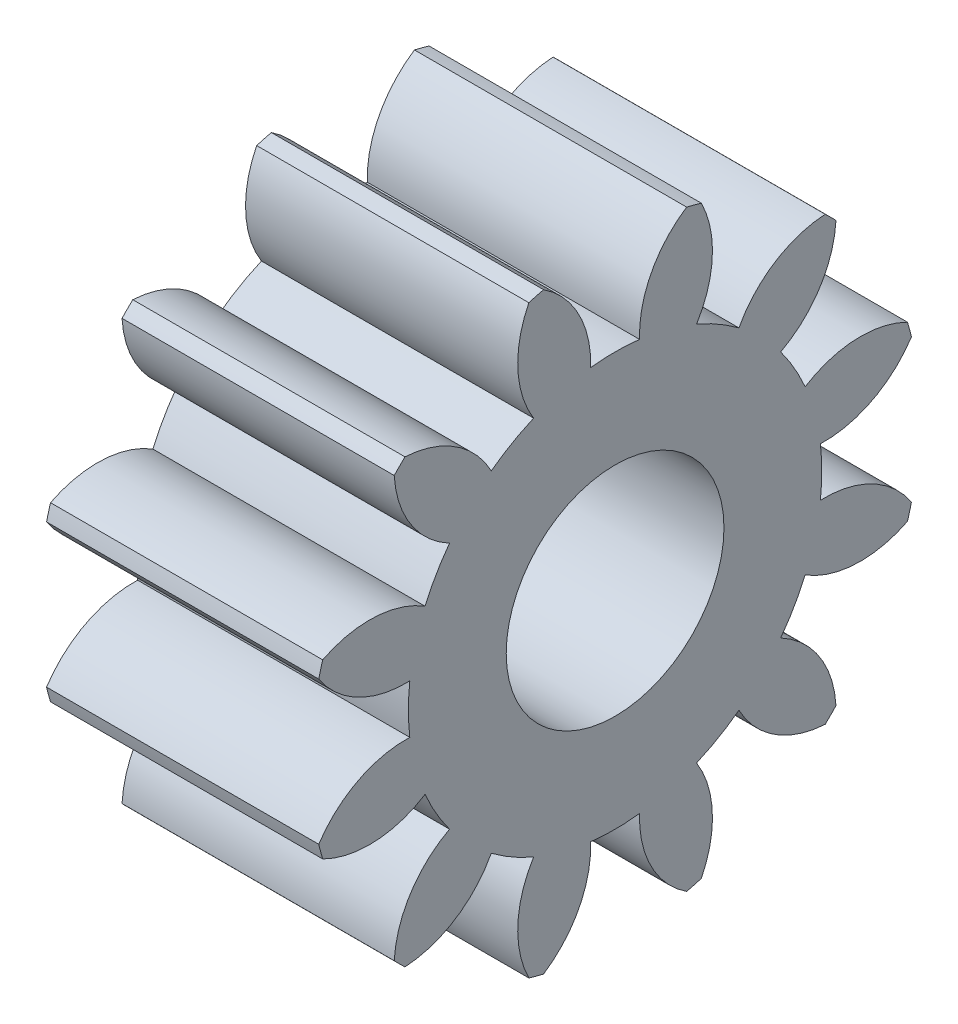
SolidWorks part; units mm, degrees
ref_plane "Plane1" through (0, 0, 0) normal (0, 0, 1) x (1, 0, 0)
ref_plane "Plane2" through (0, 0, 0) normal (0, 1, 0) x (1, 0, 0)
ref_plane "Plane3" through (0, 0, 0) normal (1, 0, 0) x (0, 0, -1)
sketch "HoldingSke" plane through (0, 0, 0) normal (0, 1, 0) x (1, 0, 0)
  line L0 (0, 0) -> (2.4454, -0.5198)
  line L1 (-15, 0) -> (100, 0) construction
  line L2 (0, 0) -> (-2.1039, 2.3779)
  line L3 (0, 0) -> (-11.863, 4.5341)
  line L4 (0, 0) -> (8.4473, 1.7955)
  line L5 (0, 0) -> (-46.8476, -17.4728)
  line L6 (0, 0) -> (-2.0724, -1.3983)
  line L7 (-2.1039, 2.3779) -> (8.6586, 51.2059)
  line L8 (-76.2, 54.61) -> (-75.9, 54.61)
  line L9 (-71.009, 38.7566) -> (-53.1078, 45.2721)
  line L10 (-76.2, 71.12) -> (104.1128, 71.12)
  line L11 (0, 0) -> (-2.5, 0)
  line L12 (-76.2, 101.6) -> (-76.185, 101.6)
  line L13 (24.9733, 27.94) -> (52.9518, 28.4284)
  line L14 (24.9733, 27.94) -> (24.9743, 27.94)
  line L15 (24.9733, 27.94) -> (100.4006, 29.5858)
  line L16 (-63.627, -0.4) -> (-12.827, -0.4)
  circle A0 centre (0, 0) radius 1
  circle A1 centre (0, 0) radius 1.899
  circle A2 centre (0, 0) radius 37.5
  circle A3 centre (0, 0) radius 1
  dimension "MHD" = 3.798
  dimension "Hub_dia" = 75
  dimension "Bore" = 2
  dimension "MBD" = 2
  dimension "Num_teeth" = 12
  dimension "Pitch" = 2.5
  dimension "Overall_len" = 50
  dimension "Show_teeth" = 12
  dimension "Thickness" = 2.5
  dimension "OAL" = 50.0001
  dimension "T_dim" = 0.3
  dimension "Ap" = 20
  dimension "H" = 19.05
  dimension "Pitch_radius" = 180.3128
  dimension "Width" = 2.5
  dimension "Backlash" = 0.015
  dimension "Addendum_fac" = 1
  dimension "Dedendum_fac" = 1.25
  dimension "Clearance_fac" = 0.25
  dimension "Dedendum_add" = 0.001
  dimension "Module" = 0.4
sketch "BasProSke" plane through (0, 0, 0) normal (0, 1, 0) x (1, 0, 0)
  line L0 (-10, 0) -> (60, 0) construction
  line L1 (0, 0) -> (0, 2.8)
  line L2 (0, 0) -> (2.5, 0)
  line L3 (2.5, 0) -> (2.5, 2.8)
  line L4 (2.5, 2.8) -> (0, 2.8)
  dimension "Thickness" = 2.5
  dimension "Diameter" = 5.6
revolve "Base-Revolve" add sketch "BasProSke" angle 360 about L0
sketch "TooCutSke" plane through (0, 0, 0) normal (1, 0, 0) x (0, 0, -1)
  line L1 (0, 0) -> (0, 107) construction
  line L2 (0, 0) -> (-0.3395, 2.3759) construction
  line L3 (0, 0) -> (-1.2334, 4.6032) construction
  line L4 (-0.3395, 2.3759) -> (-0.6167, 2.3016) construction
  arc A0 (0.2246, 1.8857) -> (-0.2246, 1.8857) centre (0, 0) ccw
  arc A1 (0.6868, 2.7407) -> (-0.6868, 2.7407) centre (0, 0) ccw
  circle A2 centre (0, 0) radius 2.4 construction
  circle A3 centre (0, 0) radius 2.2553 construction
  arc A4 (-0.2246, 1.8857) -> (-0.6868, 2.7407) centre (-1.184, 1.9194) ccw
  arc A5 (0.6868, 2.7407) -> (0.2246, 1.8857) centre (1.184, 1.9194) ccw
  dimension "Root_dia" = 3.798
  dimension "Overcut_dia" = 5.6508
  dimension "Pitch_dia" = 4.8
  dimension "Base_dia" = 4.5105
  dimension "Flank_rad" = 0.96
  dimension "Half_ang" = 15
  dimension "Half_CT" = 0.287
extrude "ToothCut" cut sketch "TooCutSke" along normal through all
fillet "Breaks" [suppressed] radius 0.008
fillet "RootFillets" [suppressed] radius 0.101
pattern_circular "TeethCuts" count 12 every 30 about axis through (-10, 0, 0) along (1, 0, 0) of "ToothCut", "RootFillets", "Breaks"
sketch "HubNeaOneSke" plane through (0, 0, 0) normal (-1, 0, 0) x (0, 0, 1)
  circle A0 centre (0, 0) radius 1.899
  dimension "Diameter" = 3.798
extrude "HubNearOne" [suppressed] add sketch "HubNeaOneSke" along normal blind 47.5001
sketch "HubNeaBotSke" plane through (0, 0, 0) normal (-1, 0, 0) x (0, 0, 1)
  circle A0 centre (0, 0) radius 1.899
  dimension "Diameter" = 3.798
extrude "HubNearBoth" [suppressed] add sketch "HubNeaBotSke" along normal blind 23.75
ref_plane "FarPln" through (2.5, 0, 0) normal (1, 0, 0) x (0, 0, -1)
sketch "HubFarSke" plane through (2.5, 0, 0) normal (1, 0, 0) x (0, 0, -1)
  circle A0 centre (0, 0) radius 1.899
  dimension "Diameter" = 3.798
extrude "HubFar" [suppressed] add sketch "HubFarSke" along normal blind 23.75
sketch "BorSke" plane through (0, 0, 0) normal (1, 0, 0) x (0, 0, -1)
  circle A0 centre (0, 0) radius 1
  dimension "Diameter" = 2
extrude "Bore" cut sketch "BorSke" along normal mid plane 100.0001
sketch "KeySke" plane through (0, 0, 0) normal (1, 0, 0) x (0, 0, -1)
  line L0 (-0.4, 0) -> (-0.4, 1.3)
  line L1 (-0.4, 1.3) -> (0.4, 1.3)
  line L2 (0.4, 1.3) -> (0.4, 0)
  line L3 (0, 0) -> (0, 34) construction
  line L4 (-0.4, 0) -> (0.4, 0)
  dimension "Offset" = 1.3
  dimension "Width" = 0.8
extrude "Keyway" [suppressed] cut sketch "KeySke" along normal mid plane 100.0001
pattern_circular "Keyway2" [suppressed] count 2 every 90 about axis through (-10, 0, 0) along (1, 0, 0)
equation "' \"Module@HoldingSke\" = 6.35"
equation "' \"Num_teeth@HoldingSke\" = 12"
equation "' \"Ap@HoldingSke\" =  20"
equation "' \"Ap@HoldingSke\" = 20"
equation "' \"Width@HoldingSke\" = 0.5 * 25.4"
equation "' \"Hub_dia@HoldingSke\"= 1 * 25.4"
equation "' \"Hub_dia@HoldingSke\" = 1 * 25.4"
equation "' \"Overall_len@HoldingSke\" = 1.0 * 25.4"
equation "' \"Bore@HoldingSke\" = 0.75 * 25.4"
equation "' \"T_dim@HoldingSke\" = 0.1 * 25.4"
equation "' \"Width@KeySke\" = 0.25 * 25.4"
equation "' \"Show_teeth@HoldingSke\" = 13"
equation "' \"Backlash@HoldingSke\" = 0.009 * 25.4"
equation "' \"Addendum_fac@HoldingSke\" = 1.0"
equation "' \"Dedendum_fac@HoldingSke\" = 1.25"
equation "' \"Dedendum_add@HoldingSke\" = 0.00005 * 25.4"
equation "' \"Clearance_fac@HoldingSke\" = 0.25"
equation "\"Pitch@HoldingSke\" = 1 / \"Module@HoldingSke\""
equation "\"Overcut_dia@TooCutSke\" = (\"Num_teeth@HoldingSke\" + 2 * \"Addendum_fac@HoldingSke\") / \"Pitch@HoldingSke\" + 0.002 * 25.4"
equation "\"Pitch_dia@TooCutSke\" = \"Num_teeth@HoldingSke\" / \"Pitch@HoldingSke\""
equation "\"Base_dia@TooCutSke\" = \"Num_teeth@HoldingSke\" / \"Pitch@HoldingSke\" * cos((\"Ap@HoldingSke\"  * 3.14159265 / 180))"
equation "\"Root_dia@TooCutSke\" = (\"Num_teeth@HoldingSke\" + 2) / \"Pitch@HoldingSke\" - 2 * (\"Addendum_fac@HoldingSke\" + \"Dedendum_fac@HoldingSke\") / \"Pitch@HoldingSke\" - \"Dedendum_add@HoldingSke\" * 2"
equation "\"Half_ang@TooCutSke\" = 180 / \"Num_teeth@HoldingSke\""
equation "\"Half_CT@TooCutSke\" = \"Num_teeth@HoldingSke\" / \"Pitch@HoldingSke\" * sin((3.14159265 / 2 / \"Num_teeth@HoldingSke\")) / 2 - 7 * \"Backlash@HoldingSke\" / 4"
equation "\"Flank_rad@TooCutSke\" = \"Num_teeth@HoldingSke\" / \"Pitch@HoldingSke\" / 5"
equation "\"Radius@RootFillets\" = \"Clearance_fac@HoldingSke\" / \"Pitch@HoldingSke\" + \"Dedendum_add@HoldingSke\""
equation "\"Break_rad@Breaks\" = 0.02 / \"Pitch@HoldingSke\""
equation "\"Thickness@HoldingSke\" = \"Width@HoldingSke\""
equation "\"OAL@HoldingSke\" = \"Thickness@HoldingSke\""
equation "\"MHD@HoldingSke\" = (\"Num_teeth@HoldingSke\" + 2) / \"Pitch@HoldingSke\" - 2 * (\"Addendum_fac@HoldingSke\" + \"Dedendum_fac@HoldingSke\")  / \"Pitch@HoldingSke\" - \"Dedendum_add@HoldingSke\" * 2"
equation "\"MBD@HoldingSke\" = (\"Num_teeth@HoldingSke\" + 2) / \"Pitch@HoldingSke\" - 2 * (\"Addendum_fac@HoldingSke\" + \"Dedendum_fac@HoldingSke\")  / \"Pitch@HoldingSke\" - \"Dedendum_add@HoldingSke\" * 2 - 0.002 * 25.4"
equation "\"MHD@HoldingSke\" = ((sgn( \"MHD@HoldingSke\" - \"Hub_dia@HoldingSke\" )-1)*( \"MHD@HoldingSke\" - \"Hub_dia@HoldingSke\" ))/-2+ \"Hub_dia@HoldingSke\""
equation "\"MBD@HoldingSke\" = ((sgn( \"MBD@HoldingSke\" - \"Bore@HoldingSke\" )-1)*( \"MBD@HoldingSke\" - \"Bore@HoldingSke\" ))/-2+ \"Bore@HoldingSke\""
equation "\"OAL@HoldingSke\" = ((sgn( \"OAL@HoldingSke\" - \"Overall_len@HoldingSke\" )+1)*( \"OAL@HoldingSke\" - \"Overall_len@HoldingSke\" ))/2 + \"Overall_len@HoldingSke\" + 0.000002 * 25.4"
equation "\"Num_teeth@TeethCuts\" = int( \"Show_teeth@HoldingSke\" ) + 1"
equation "\"Num_teeth@TeethCuts\" = ((sgn( \"Num_teeth@TeethCuts\" - \"Num_teeth@HoldingSke\" )-1)*( \"Num_teeth@TeethCuts\" - \"Num_teeth@HoldingSke\" ))/-2+ \"Num_teeth@HoldingSke\""
equation "\"Num_teeth@TeethCuts\" = ((sgn( \"Num_teeth@TeethCuts\" - 2.0)+1)*( \"Num_teeth@TeethCuts\" - 2.0))/2 +2.0"
equation "\"Angle@TeethCuts\" = 360.0 / \"Num_teeth@HoldingSke\""
equation "\"Diameter@BasProSke\" = (\"Num_teeth@HoldingSke\" + 2 * \"Addendum_fac@HoldingSke\") / \"Pitch@HoldingSke\""
equation "\"Thickness@BasProSke\"  = \"Thickness@HoldingSke\""
equation "' \"Fillet_rad@BasProSke\" =  \"Thickness@HoldingSke\" * 0.05"
equation "' \"Fillet_rad@BasProSke\" = \"Thickness@HoldingSke\" * 0.05"
equation "\"MHD@HoldingSke\" = ((sgn( \"MHD@HoldingSke\" - \"Root_dia@TooCutSke\" )-1)*( \"MHD@HoldingSke\" - \"Root_dia@TooCutSke\" ))/-2+ \"Root_dia@TooCutSke\""
equation "\"Diameter@HubNeaOneSke\" = \"MHD@HoldingSke\""
equation "\"Length@HubNearOne\" = \"OAL@HoldingSke\" - \"Thickness@BasProSke\""
equation "\"Diameter@HubNeaBotSke\" = \"MHD@HoldingSke\""
equation "\"Length@HubNearBoth\" = ( \"OAL@HoldingSke\" - \"Thickness@BasProSke\" ) / 2.0"
equation "\"Thickness@FarPln\" = \"Thickness@BasProSke\""
equation "\"Diameter@HubFarSke\" = \"MHD@HoldingSke\""
equation "\"Length@HubFar\" = ( \"OAL@HoldingSke\" - \"Thickness@BasProSke\" ) / 2.0"
equation "\"Diameter@BorSke\" = \"MBD@HoldingSke\""
equation "\"D1@Bore\" = \"OAL@HoldingSke\" * 2.0"
equation "\"D1@Keyway\" = \"OAL@HoldingSke\" * 2.0"
equation "\"Offset@KeySke\" = \"T_dim@HoldingSke\" + \"MBD@HoldingSke\" / 2.0"
